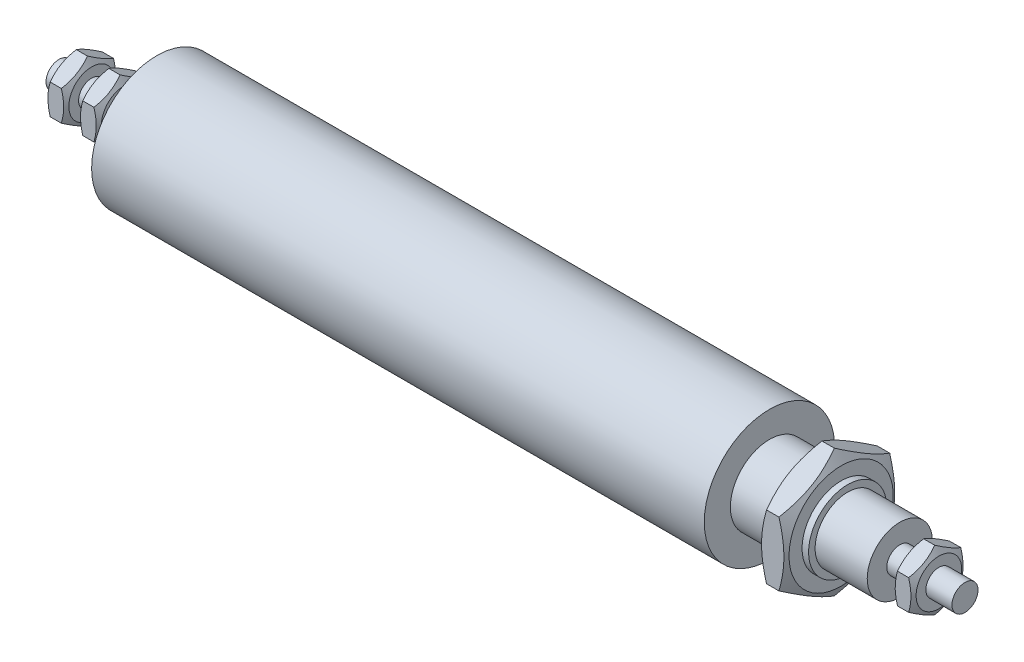
SolidWorks part; units mm, degrees
material "ASTM A36 Steel"
ref_plane "Front Plane" through (0, 0, 0) normal (0, 0, 1) x (1, 0, 0)
ref_plane "Top Plane" through (0, 0, 0) normal (0, 1, 0) x (1, 0, 0)
ref_plane "Right Plane" through (0, 0, 0) normal (1, 0, 0) x (0, 0, -1)
sketch "Sketch1" plane through (0, 0, 0) normal (0, 0, 1) x (1, 0, 0)
  line L0 (30, 0) -> (-109, 0)
  line L1 (12, 5) -> (20, 5)
  line L2 (-109, 0) -> (-109, 2)
  line L3 (-109, 2) -> (-107, 2)
  line L4 (-107, 2) -> (-107, 3.5)
  line L5 (-107, 3.5) -> (-105.5, 6.0981)
  line L6 (20, 5) -> (20, 2)
  line L7 (-105.5, 6.0981) -> (-104, 3.5)
  line L8 (-104, 3.5) -> (-104, 2)
  line L9 (-104, 2) -> (-102, 2)
  line L10 (-102, 2) -> (-102, 3.5)
  line L11 (-102, 3.5) -> (-100.5, 6.0981)
  line L13 (-100.5, 6.0981) -> (-99, 3.5)
  line L14 (-99, 3.5) -> (-99, 2)
  line L15 (-99, 2) -> (-94, 2)
  line L16 (-94, 2) -> (-94, 10)
  line L17 (-94, 10) -> (0, 10)
  line L18 (0, 10) -> (0, 6)
  line L19 (0, 6) -> (7, 6)
  line L20 (7, 6) -> (7, 8)
  line L21 (7, 8) -> (9, 11.4641)
  line L23 (9, 11.4641) -> (11, 8)
  line L24 (11, 8) -> (11, 6)
  line L25 (11, 6) -> (12, 6)
  line L26 (12, 6) -> (12, 5)
  line L27 (20, 2) -> (23, 2)
  line L28 (23, 2) -> (23, 3.5)
  line L29 (23, 3.5) -> (24.5, 6.0981)
  line L31 (24.5, 6.0981) -> (26, 3.5)
  line L32 (26, 3.5) -> (26, 2)
  line L33 (26, 2) -> (30, 2)
  line L34 (30, 2) -> (30, 0)
  line L35 (30, 0) -> (40.1315, 0) construction
  dimension "D1" = 4
  dimension "D2" = 20
  dimension "D3" = 30
  dimension "D4" = 2
  dimension "D5" = 3
  dimension "D6" = 30
  dimension "D7" = 2
  dimension "D8" = 7
  dimension "D9" = 10
  dimension "D10" = 4
  dimension "D11" = 3
  dimension "D12" = 94
  dimension "D13" = 12
  dimension "D14" = 4
  dimension "D15" = 7
  dimension "D16" = 16
  dimension "D17" = 7
  dimension "D18" = 4
  dimension "D19" = 12
  dimension "D20" = 18
  dimension "D21" = 139
  dimension "D22" = 10
revolve "Revolve1" add sketch "Sketch1" angle 360 about L35
sketch "Sketch2" plane through (26, 0, 0) normal (1, 0, 0) x (0, 0, -1)
  line L1 (0, -4.6188) -> (4, -2.3094)
  line L2 (4, -2.3094) -> (4, 2.3094)
  line L3 (4, 2.3094) -> (0, 4.6188)
  line L4 (0, 4.6188) -> (-4, 2.3094)
  line L5 (-4, 2.3094) -> (-4, -2.3094)
  line L6 (-4, -2.3094) -> (0, -4.6188)
  circle A0 centre (0, 0) radius 4 construction
  circle A1 centre (0, 0) radius 3.5 construction
  dimension "D1" = 0.5
extrude "Cut-Extrude1" cut sketch "Sketch2" against normal up to surface (3 mm away) flip side to cut up to face at (23, 0, 2)
sketch "Sketch3" plane through (11, 0, 0) normal (1, 0, 0) x (0, 0, -1)
  line L1 (0, 9.815) -> (-8.5, 4.9075)
  line L2 (-8.5, 4.9075) -> (-8.5, -4.9075)
  line L3 (-8.5, -4.9075) -> (0, -9.815)
  line L4 (0, -9.815) -> (8.5, -4.9075)
  line L5 (8.5, -4.9075) -> (8.5, 4.9075)
  line L6 (8.5, 4.9075) -> (0, 9.815)
  circle A0 centre (0, 0) radius 8.5 construction
  circle A1 centre (0, 0) radius 8 construction
  dimension "D1" = 0.5
extrude "Cut-Extrude2" cut sketch "Sketch3" against normal up to surface (4 mm away) flip side to cut up to face at (7, 0, 6)
sketch "Sketch4" plane through (-107, 0, 0) normal (-1, 0, 0) x (0, 0, 1)
  line L1 (0, 4.6188) -> (-4, 2.3094)
  line L2 (-4, 2.3094) -> (-4, -2.3094)
  line L3 (-4, -2.3094) -> (0, -4.6188)
  line L4 (0, -4.6188) -> (4, -2.3094)
  line L5 (4, -2.3094) -> (4, 2.3094)
  line L6 (4, 2.3094) -> (0, 4.6188)
  circle A0 centre (0, 0) radius 4 construction
  circle A1 centre (0, 0) radius 3.5 construction
  dimension "D1" = 0.5
extrude "Cut-Extrude3" cut sketch "Sketch4" against normal up to surface (8 mm away) flip side to cut up to face at (-99, 0, 3.5)
